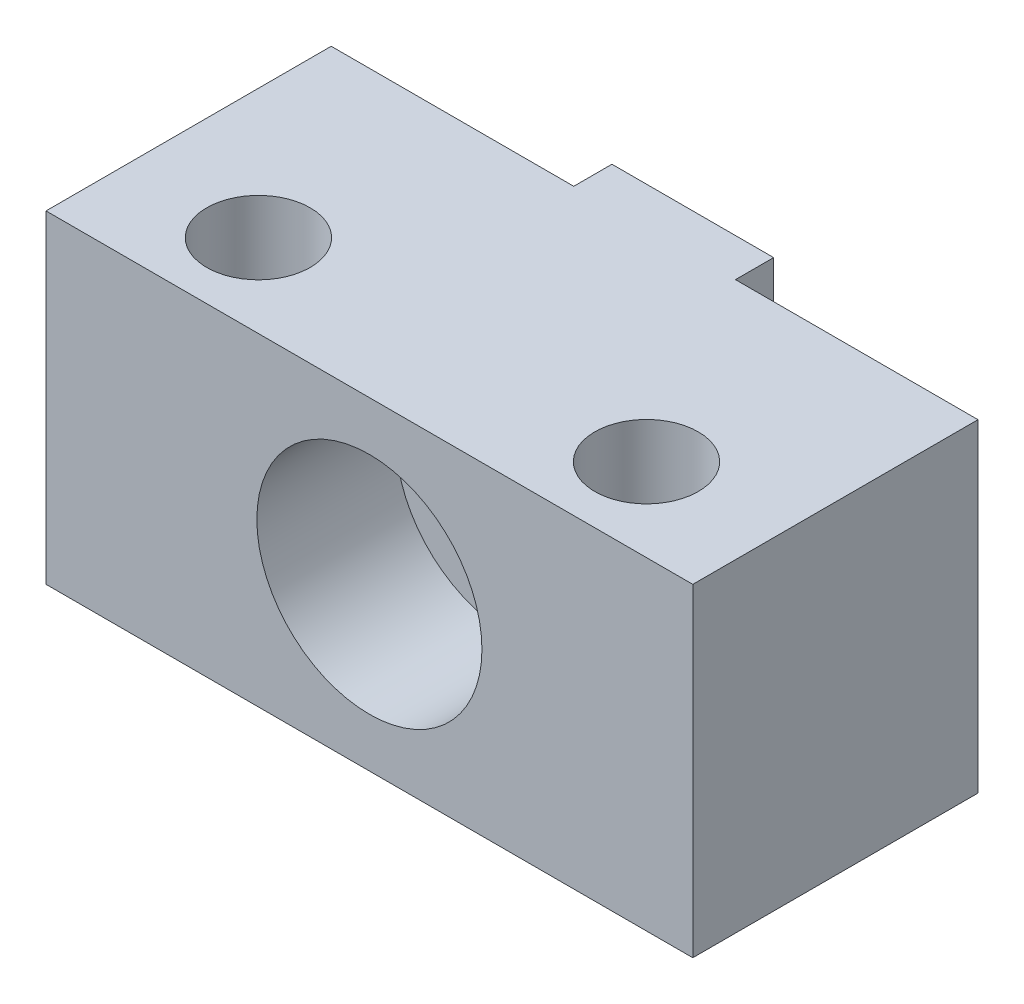
SolidWorks part; units mm, degrees
ref_plane "Front Plane" through (0, 0, 0) normal (0, 0, 1) x (1, 0, 0)
ref_plane "Top Plane" through (0, 0, 0) normal (0, 1, 0) x (1, 0, 0)
ref_plane "Right Plane" through (0, 0, 0) normal (1, 0, 0) x (0, 0, -1)
ref_plane "Plane1" through (0, 12.7, 0) normal (0, 1, 0) x (1, 0, 0)
sketch "Sketch1" plane through (0, 12.7, 0) normal (0, 1, 0) x (1, 0, 0)
  line L0 (12.7, -11.2) -> (12.7, 1.5)
  line L1 (12.7, 1.5) -> (-12.7, 1.5)
  line L2 (-12.7, 1.5) -> (-12.7, -11.2)
  line L3 (-12.7, -11.2) -> (12.7, -11.2)
extrude "Boss-Extrude1" add sketch "Sketch1" against normal blind 12.7
sketch "Sketch2" plane through (0, 0, 0) normal (0, -1, 0) x (1, 0, 0)
  line L0 (12.7, -1.5) -> (12.7, 0)
  line L1 (12.7, 0) -> (3.175, 0)
  line L2 (3.175, 0) -> (3.175, -1.5)
  line L3 (3.175, -1.5) -> (12.7, -1.5)
extrude "Cut-Extrude1" cut sketch "Sketch2" against normal through all
sketch "Sketch3" plane through (0, 0, 0) normal (0, -1, 0) x (1, 0, 0)
  line L0 (-12.7, -1.5) -> (-3.175, -1.5)
  line L1 (-3.175, -1.5) -> (-3.175, 0)
  line L2 (-3.175, 0) -> (-12.7, 0)
  line L3 (-12.7, 0) -> (-12.7, -1.5)
extrude "Cut-Extrude2" cut sketch "Sketch3" against normal through all
hole_wizard "#6 Clearance Hole1" positions "Sketch5" profile "Sketch4" hole size "#6" standard "ANSI Inch"
sketch "Sketch5" plane through (0, 0, 0) normal (0, -1, 0) x (-1, 0, 0)
  point P0 (7.62, -7.9375)
  point P1 (-7.62, -7.9375)
sketch "Sketch4" plane through (-7.62, 0, 7.9375) normal (1, 0, 0) x (0, 0, -1)
  line L0 (0, 0) -> (0, 12.7)
  line L1 (0, 12.7) -> (2.032, 12.7)
  line L2 (2.032, 12.7) -> (2.032, 0)
  line L5 (2.032, 0) -> (0, 0)
  line L11 (0, -6.35) -> (0, 107.95) construction
  dimension "Thru Hole Dia." = 4.064
  dimension "Thru Hole Depth" = 12.7
hole_wizard "CBORE for #10 Binding Head Machine Screw1" positions "Sketch7" profile "Sketch6" counterbore size "#10" standard "ANSI Inch"
sketch "Sketch7" plane through (0, 0, 11.2) normal (0, 0, 1) x (1, 0, 0)
  point P0 (0, 6.35)
sketch "Sketch6" plane through (0, 6.35, 11.2) normal (1, 0, 0) x (0, -1, 0)
  line L0 (0, 0) -> (0, 12.7)
  line L1 (0, 12.7) -> (2.5, 12.7)
  line L3 (2.5, 12.7) -> (2.5, 5.461)
  line L4 (2.5, 5.461) -> (4.4196, 5.461)
  line L5 (4.4196, 5.461) -> (4.4196, 0)
  line L7 (4.4196, 0) -> (0, 0)
  line L11 (0, -6.35) -> (0, 107.95) construction
  dimension "Thru Hole Dia." = 5
  dimension "Thru Hole Depth" = 12.7
  dimension "C'Bore Dia." = 8.8392
  dimension "C'Bore Depth" = 5.461
